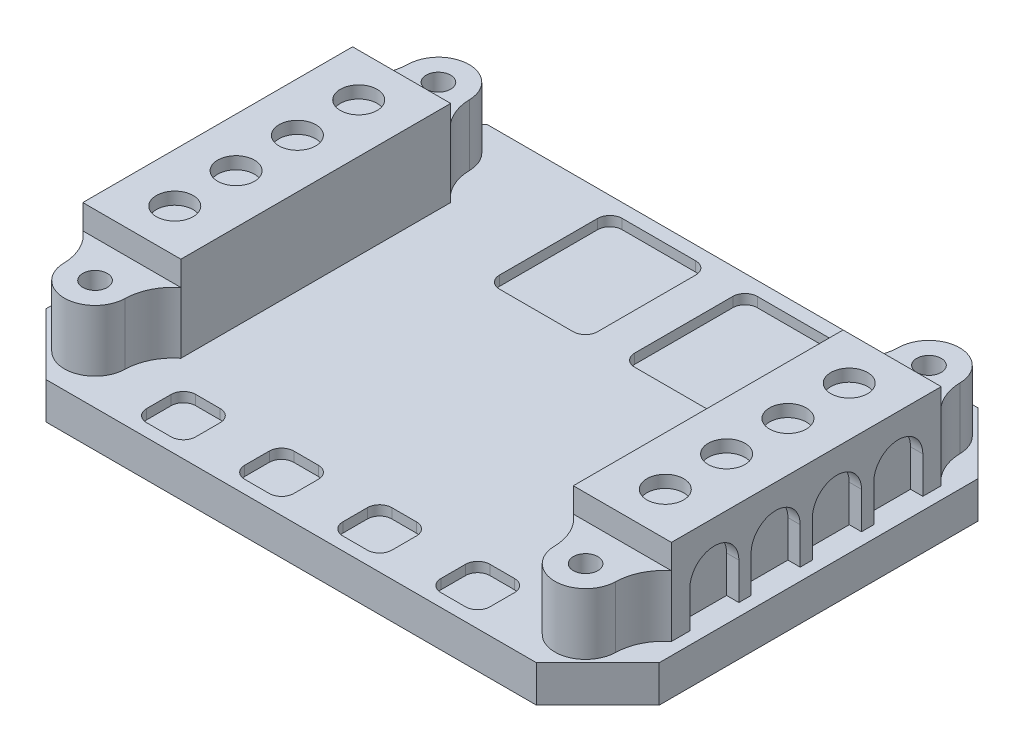
SolidWorks part; units mm, degrees
ref_plane "Alzado" through (0, 0, 0) normal (0, 0, 1) x (1, 0, 0)
ref_plane "Planta" through (0, 0, 0) normal (0, 1, 0) x (1, 0, 0)
ref_plane "Vista lateral" through (0, 0, 0) normal (1, 0, 0) x (0, 0, -1)
sketch "Croquis1" plane through (0, 0, 0) normal (0, 1, 0) x (1, 0, 0)
  line L0 (-25, -13) -> (-20, -18)
  line L1 (-20, 18) -> (20, 18)
  line L2 (-25, 13) -> (-25, -13)
  line L3 (-20, -18) -> (20, -18)
  line L4 (25, 13) -> (25, -13)
  line L5 (-25, 18) -> (25, -18) construction
  line L6 (-25, -18) -> (25, 18) construction
  line L7 (-25, 13) -> (-20, 18)
  line L8 (20, 18) -> (25, 13)
  line L9 (20, -18) -> (25, -13)
  point P0 (0, 0)
  dimension "D1" = 50
  dimension "D2" = 36
extrude "Saliente-Extruir1" add sketch "Croquis1" along normal blind 3
sketch "Croquis2" plane through (0, 3, 0) normal (0, 1, 0) x (1, 0, 0)
  line L0 (-25, 13) -> (-25, -13) construction
  line L1 (0, 10.1526) -> (0, 0) construction
  line L2 (-24, 11) -> (-24, -11)
  line L4 (-16, 11) -> (-16, -11)
  line L5 (-24, 11) -> (-16, -11) construction
  line L6 (-24, -11) -> (-16, 11) construction
  line L14 (-20, -18) -> (20, -18) construction
  arc A0 (-22.4995, -14.0475) -> (-17.5005, -14.0475) centre (-20, -14) ccw
  circle A1 centre (-20, -14) radius 1
  arc A2 (-22.4995, -14.0475) -> (-24, -11) centre (-26.4988, -14.1234) ccw
  arc A3 (-16, -11) -> (-17.5005, -14.0475) centre (-13.5012, -14.1234) ccw
  arc A4 (-16, 11) -> (-17.5005, 14.0475) centre (-13.5012, 14.1234) cw
  circle A5 centre (-20, 14) radius 1
  arc A6 (-22.4995, 14.0475) -> (-17.5005, 14.0475) centre (-20, 14) cw
  arc A7 (-22.4995, 14.0475) -> (-24, 11) centre (-26.4988, 14.1234) cw
  point P0 (-20, 0)
  dimension "D7" = 5
  dimension "D9" = 8
  dimension "D10" = 8
  dimension "D11" = 2
  dimension "D2" = 8
  dimension "D3" = 5
  dimension "D8" = 4
extrude "Saliente-Extruir2" add sketch "Croquis2" along normal blind 7
sketch "Croquis3" plane through (0, 10, 0) normal (0, 1, 0) x (1, 0, 0)
  line L1 (-24, -11) -> (-15.4156, -11)
  line L2 (-24, -11) -> (-24, -17.2453)
  line L3 (-24, -17.2453) -> (-15.4156, -17.2453)
  line L4 (-15.4156, -11) -> (-15.4156, -17.2453)
  line L13 (-16, 11) -> (-25.1038, 11)
  line L14 (-16, 11) -> (-16, 17.5236)
  line L15 (-16, 17.5236) -> (-25.1038, 17.5236)
  line L16 (-25.1038, 11) -> (-25.1038, 17.5236)
extrude "Cortar-Extruir1" cut sketch "Croquis3" against normal blind 2
sketch "Croquis4" plane through (0, 10, 0) normal (0, 1, 0) x (1, 0, 0)
  line L0 (-24, 11) -> (-24, -11) construction
  line L1 (-24, 11) -> (-16, 11) construction
  circle A0 centre (-20, 7.5) radius 1.5
  circle A1 centre (-20, 2.5) radius 1.5
  circle A2 centre (-20, -2.5) radius 1.5
  circle A3 centre (-20, -7.5) radius 1.5
  dimension "D1" = 3
  dimension "D2" = 4
  dimension "D3" = 3.5
  dimension "D4" = 4
extrude "Cortar-Extruir2" cut sketch "Croquis4" against normal blind 1
sketch "Croquis5" plane through (-24, 0, 0) normal (-1, 0, 0) x (0, 0, 1)
  line L0 (-11, 8) -> (-11, 3) construction
  line L1 (-13, 3) -> (13, 3) construction
  line L2 (-9.5, 6) -> (-9.5, 3)
  line L3 (-11, 3) -> (11, 3) construction
  line L4 (-9.5, 3) -> (-5.5, 3)
  line L5 (-5.5, 3) -> (-5.5, 6)
  line L6 (-0.5, 3) -> (-0.5, 6)
  line L7 (-4.5, 3) -> (-0.5, 3)
  line L8 (-4.5, 6) -> (-4.5, 3)
  line L9 (4.5, 3) -> (4.5, 6)
  line L10 (0.5, 3) -> (4.5, 3)
  line L11 (0.5, 6) -> (0.5, 3)
  line L12 (9.5, 3) -> (9.5, 6)
  line L13 (5.5, 3) -> (9.5, 3)
  line L14 (5.5, 6) -> (5.5, 3)
  arc A0 (-5.5, 6) -> (-9.5, 6) centre (-7.5, 6) ccw
  arc A1 (-0.5, 6) -> (-4.5, 6) centre (-2.5, 6) ccw
  arc A2 (4.5, 6) -> (0.5, 6) centre (2.5, 6) ccw
  arc A3 (9.5, 6) -> (5.5, 6) centre (7.5, 6) ccw
  dimension "D1" = 4
  dimension "D2" = 3.5
  dimension "D3" = 3
  dimension "D4" = 4
extrude "Cortar-Extruir3" cut sketch "Croquis5" against normal blind 1
mirror "Simetría1" about plane through (0, 0, 0) normal (1, 0, 0) of "Cortar-Extruir3", "Cortar-Extruir2", "Cortar-Extruir1", "Saliente-Extruir2"
sketch "Croquis6" plane through (0, 3, 0) normal (0, 1, 0) x (1, 0, 0)
  line L0 (-4.8495, -12.9449) -> (-2.8495, -12.9449)
  line L1 (-7.8893, 16.8731) -> (-1.8893, 16.8731)
  line L2 (-8.8893, 15.8731) -> (-8.8893, 7.8731)
  line L3 (-7.8893, 6.8731) -> (-1.8893, 6.8731)
  line L4 (-0.8893, 15.8731) -> (-0.8893, 7.8731)
  line L5 (3.1305, 16.8731) -> (9.1305, 16.8731)
  line L6 (2.1305, 15.8731) -> (2.1305, 7.8731)
  line L7 (3.1305, 6.8731) -> (9.1305, 6.8731)
  line L8 (10.1305, 15.8731) -> (10.1305, 7.8731)
  line L9 (-12.8495, -12.9449) -> (-10.8495, -12.9449)
  line L10 (-13.8495, -13.9449) -> (-13.8495, -15.9449)
  line L11 (-12.8495, -16.9449) -> (-10.8495, -16.9449)
  line L12 (-9.8495, -13.9449) -> (-9.8495, -15.9449)
  line L13 (-1.8495, -13.9449) -> (-1.8495, -15.9449)
  line L14 (-5.8495, -13.9449) -> (-5.8495, -15.9449)
  line L15 (-4.8495, -16.9449) -> (-2.8495, -16.9449)
  line L16 (3.1505, -12.9449) -> (5.1505, -12.9449)
  line L17 (6.1505, -13.9449) -> (6.1505, -15.9449)
  line L18 (2.1505, -13.9449) -> (2.1505, -15.9449)
  line L19 (3.1505, -16.9449) -> (5.1505, -16.9449)
  line L20 (11.1505, -12.9449) -> (13.1505, -12.9449)
  line L21 (14.1505, -13.9449) -> (14.1505, -15.9449)
  line L22 (10.1505, -13.9449) -> (10.1505, -15.9449)
  line L23 (11.1505, -16.9449) -> (13.1505, -16.9449)
  arc A0 (-13.8495, -15.9449) -> (-12.8495, -16.9449) centre (-12.8495, -15.9449) ccw
  arc A1 (-10.8495, -16.9449) -> (-9.8495, -15.9449) centre (-10.8495, -15.9449) ccw
  arc A2 (-10.8495, -12.9449) -> (-9.8495, -13.9449) centre (-10.8495, -13.9449) cw
  arc A3 (-12.8495, -12.9449) -> (-13.8495, -13.9449) centre (-12.8495, -13.9449) ccw
  arc A4 (2.1305, 7.8731) -> (3.1305, 6.8731) centre (3.1305, 7.8731) ccw
  arc A5 (9.1305, 6.8731) -> (10.1305, 7.8731) centre (9.1305, 7.8731) ccw
  arc A6 (9.1305, 16.8731) -> (10.1305, 15.8731) centre (9.1305, 15.8731) cw
  arc A7 (3.1305, 16.8731) -> (2.1305, 15.8731) centre (3.1305, 15.8731) ccw
  arc A8 (-7.8893, 16.8731) -> (-8.8893, 15.8731) centre (-7.8893, 15.8731) ccw
  arc A9 (-1.8893, 16.8731) -> (-0.8893, 15.8731) centre (-1.8893, 15.8731) cw
  arc A10 (-1.8893, 6.8731) -> (-0.8893, 7.8731) centre (-1.8893, 7.8731) ccw
  arc A11 (-8.8893, 7.8731) -> (-7.8893, 6.8731) centre (-7.8893, 7.8731) ccw
  arc A12 (-4.8495, -12.9449) -> (-5.8495, -13.9449) centre (-4.8495, -13.9449) ccw
  arc A13 (-2.8495, -12.9449) -> (-1.8495, -13.9449) centre (-2.8495, -13.9449) cw
  arc A14 (-2.8495, -16.9449) -> (-1.8495, -15.9449) centre (-2.8495, -15.9449) ccw
  arc A15 (-5.8495, -15.9449) -> (-4.8495, -16.9449) centre (-4.8495, -15.9449) ccw
  arc A16 (3.1505, -12.9449) -> (2.1505, -13.9449) centre (3.1505, -13.9449) ccw
  arc A17 (5.1505, -12.9449) -> (6.1505, -13.9449) centre (5.1505, -13.9449) cw
  arc A18 (5.1505, -16.9449) -> (6.1505, -15.9449) centre (5.1505, -15.9449) ccw
  arc A19 (2.1505, -15.9449) -> (3.1505, -16.9449) centre (3.1505, -15.9449) ccw
  arc A20 (11.1505, -12.9449) -> (10.1505, -13.9449) centre (11.1505, -13.9449) ccw
  arc A21 (13.1505, -12.9449) -> (14.1505, -13.9449) centre (13.1505, -13.9449) cw
  arc A22 (13.1505, -16.9449) -> (14.1505, -15.9449) centre (13.1505, -15.9449) ccw
  arc A23 (10.1505, -15.9449) -> (11.1505, -16.9449) centre (11.1505, -15.9449) ccw
  point P26 (-13.8495, -16.9449)
  point P29 (-9.8495, -16.9449)
  point P36 (2.1305, 6.8731)
  point P39 (10.1305, 6.8731)
  point P46 (-8.8893, 16.8731)
  point P51 (-0.8893, 6.8731)
  point P54 (-8.8893, 6.8731)
  dimension "D6" = 1
  dimension "D1" = 8
  dimension "D2" = 10
  dimension "D3" = 8
  dimension "D4" = 4
  dimension "D5" = 4
extrude "Cortar-Extruir4" cut sketch "Croquis6" against normal blind 0.8
